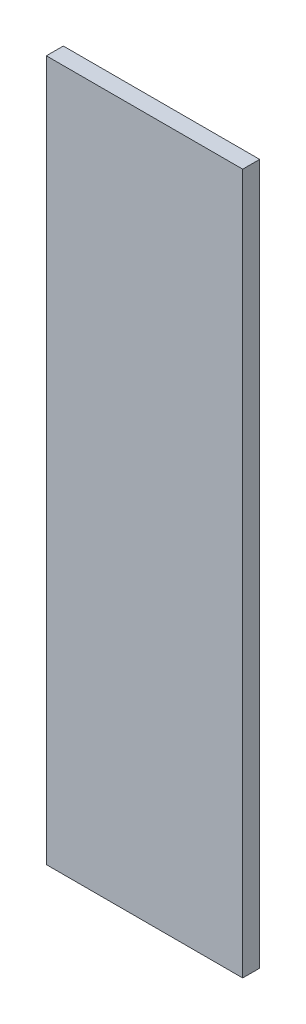
SolidWorks part; units mm, degrees
ref_plane "Front Plane" through (0, 0, 0) normal (0, 0, 1) x (1, 0, 0)
ref_plane "Top Plane" through (0, 0, 0) normal (0, 1, 0) x (1, 0, 0)
ref_plane "Right Plane" through (0, 0, 0) normal (1, 0, 0) x (0, 0, -1)
sketch "Sketch1" plane through (0, 0, 0) normal (0, 0, 1) x (1, 0, 0)
  line L1 (0, 0) -> (220.726, 0)
  line L2 (0, 0) -> (0, 787.4)
  line L3 (0, 787.4) -> (220.726, 787.4)
  line L4 (220.726, 0) -> (220.726, 787.4)
  dimension "D1" = 220.726
  dimension "D2" = 787.4
extrude "Boss-Extrude1" add sketch "Sketch1" along normal blind 19.05
